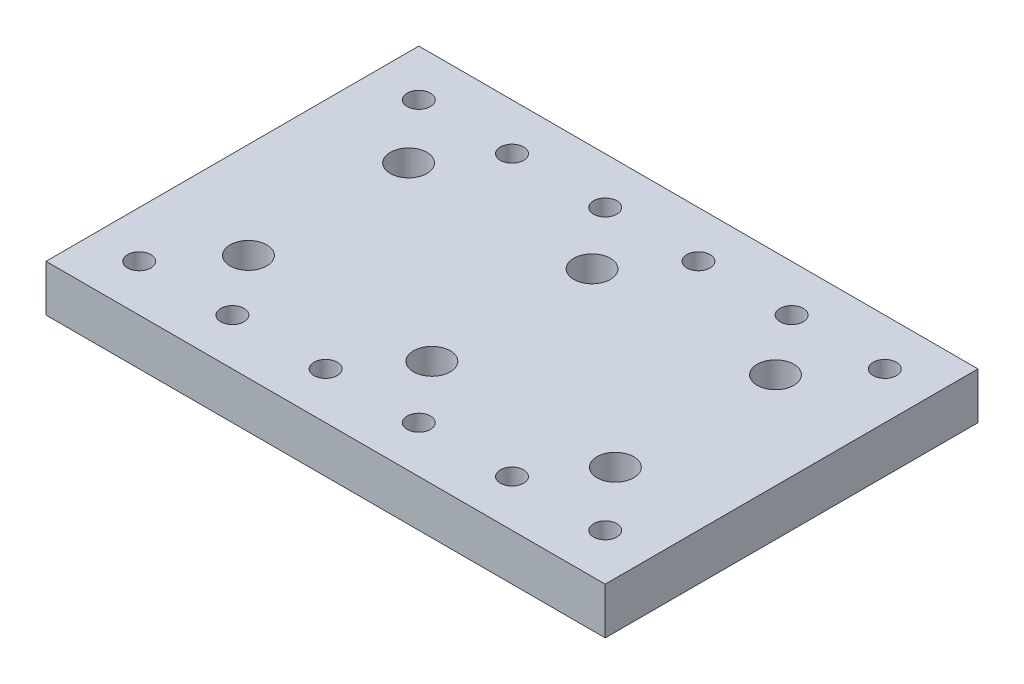
SolidWorks part; units mm, degrees
ref_plane "Front Plane" through (0, 0, 0) normal (0, 0, 1) x (1, 0, 0)
ref_plane "Top Plane" through (0, 0, 0) normal (0, 1, 0) x (1, 0, 0)
ref_plane "Right Plane" through (0, 0, 0) normal (1, 0, 0) x (0, 0, -1)
sketch "Sketch1" plane through (0, 0, 0) normal (0, 1, 0) x (1, 0, 0)
  line L1 (-76.2, -50.8) -> (76.2, -50.8)
  line L2 (-76.2, -50.8) -> (-76.2, 50.8)
  line L3 (-76.2, 50.8) -> (76.2, 50.8)
  line L4 (76.2, -50.8) -> (76.2, 50.8)
  line L5 (-76.2, -50.8) -> (76.2, 50.8) construction
  line L6 (-76.2, 50.8) -> (76.2, -50.8) construction
  point P0 (0, 0)
  dimension "D1" = 152.4
  dimension "D2" = 101.6
extrude "Boss-Extrude1" add sketch "Sketch1" along normal blind 12.7
sketch "Sketch2" plane through (0, 0, 0) normal (0, -1, 0) x (1, 0, 0)
  line L0 (-76.2, 21.825) -> (76.2, 21.825) construction
  line L2 (-76.2, -21.825) -> (76.2, -21.825) construction
  line L4 (-76.2, -50.8) -> (-76.2, 50.8) construction
  line L5 (-76.2, 50.8) -> (-76.2, 21.825) construction
  line L7 (-76.2, -21.825) -> (-76.2, -50.8) construction
  line L9 (76.2, 50.8) -> (76.2, -50.8) construction
  circle A0 centre (-50.0042, 21.825) radius 5
  circle A1 centre (-50.0042, -21.825) radius 5
  circle A2 centre (-0.0042, 21.825) radius 5
  circle A3 centre (-0.0042, -21.825) radius 5
  circle A4 centre (49.9958, 21.825) radius 5
  circle A5 centre (49.9958, -21.825) radius 5
  dimension "D2" = 50
  dimension "D3" = 50
  dimension "D4" = 10
  dimension "D1" = 43.65
extrude "Cut-Extrude1" cut sketch "Sketch2" against normal blind 12.7
sketch "Sketch3" plane through (0, 12.7, 0) normal (0, 1, 0) x (1, 0, 0)
  line L1 (-76.2, 50.8) -> (-76.2, -50.8) construction
  line L2 (76.2, -50.8) -> (76.2, 50.8) construction
  line L4 (-76.2, 0) -> (76.2, 0) construction
  circle A0 centre (-63.5, -38.1) radius 3.175
  circle A1 centre (-38.1, -38.1) radius 3.175
  circle A2 centre (-12.7, -38.1) radius 3.175
  circle A3 centre (12.7, -38.1) radius 3.175
  circle A4 centre (38.1, -38.1) radius 3.175
  circle A5 centre (63.5, -38.1) radius 3.175
  circle A6 centre (-38.1, 38.1) radius 3.175
  circle A7 centre (-12.7, 38.1) radius 3.175
  circle A8 centre (12.7, 38.1) radius 3.175
  circle A9 centre (38.1, 38.1) radius 3.175
  circle A10 centre (63.5, 38.1) radius 3.175
  circle A11 centre (-63.5, 38.1) radius 3.175
  dimension "D2" = 6.35
  dimension "D1" = 38.1
  dimension "D3" = 12.7
  dimension "D6" = 25.4
  dimension "D7" = 76.2
  dimension "D4" = 6
  dimension "D5" = 2
extrude "Cut-Extrude2" cut sketch "Sketch3" against normal through all
